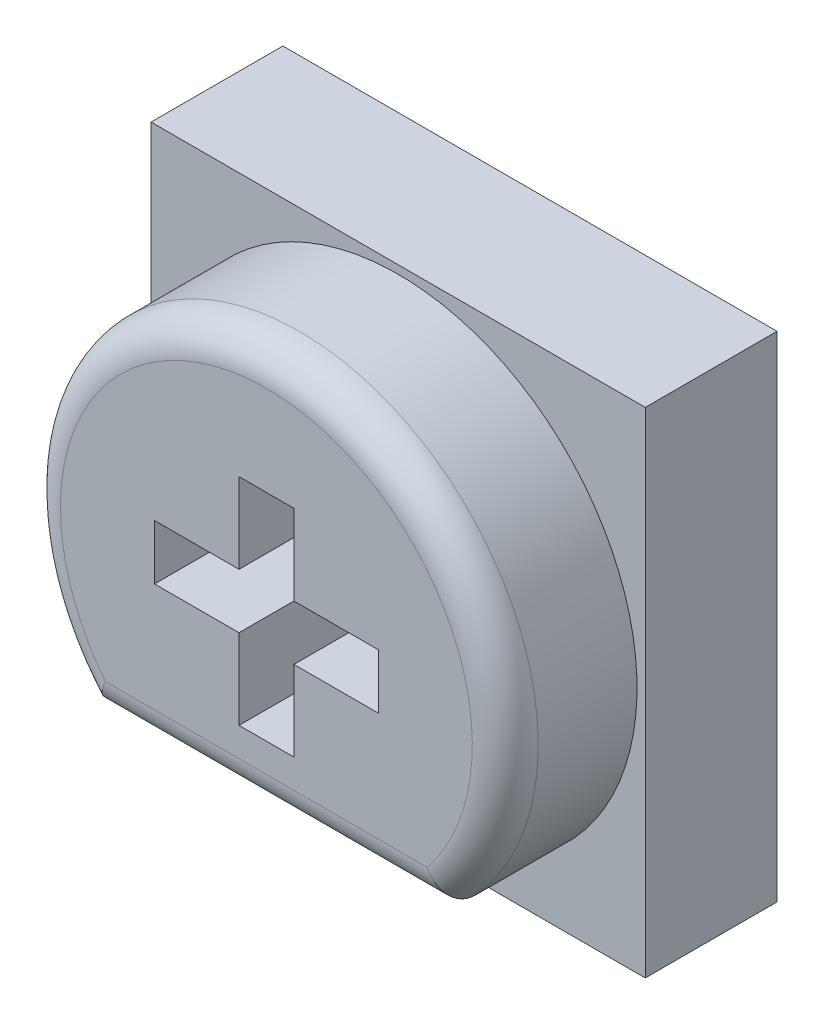
SolidWorks part; units mm, degrees
ref_plane "Front Plane" through (0, 0, 0) normal (0, 0, 1) x (1, 0, 0)
ref_plane "Top Plane" through (0, 0, 0) normal (0, 1, 0) x (1, 0, 0)
ref_plane "Right Plane" through (0, 0, 0) normal (1, 0, 0) x (0, 0, -1)
sketch "Sketch1" plane through (0, 0, 0) normal (0, 0, 1) x (1, 0, 0)
  line L1 (-1.5, 1.5) -> (1.5, 1.5)
  line L2 (-1.5, 1.5) -> (-1.5, -1.5)
  line L3 (-1.5, -1.5) -> (1.5, -1.5)
  line L4 (1.5, 1.5) -> (1.5, -1.5)
  line L5 (-1.5, 1.5) -> (1.5, -1.5) construction
  line L6 (-1.5, -1.5) -> (1.5, 1.5) construction
  point P0 (0, 0)
  dimension "D1" = 3
  dimension "D2" = 3
extrude "Boss-Extrude1" add sketch "Sketch1" along normal blind 0.8
sketch "Sketch2" plane through (0, 0, 0.8) normal (0, 0, 1) x (1, 0, 0)
  line L0 (-1.0686, -0.9801) -> (1.0686, -0.9801)
  arc A0 (1.0686, -0.9801) -> (-1.0686, -0.9801) centre (0, 0) ccw
  dimension "D1" = 2.9
extrude "Boss-Extrude2" add sketch "Sketch2" along normal blind 0.8
sketch "Sketch3" plane through (0, 0, 1.6) normal (0, 0, 1) x (1, 0, 0)
  text T0 "+" font "Century Gothic" height 2
extrude "Cut-Extrude1" cut sketch "Sketch3" against normal blind 0.8
fillet "Fillet1" radius 0.2 2 edges at (0, -0.9801, 1.6) (0, 1.45, 1.6)
